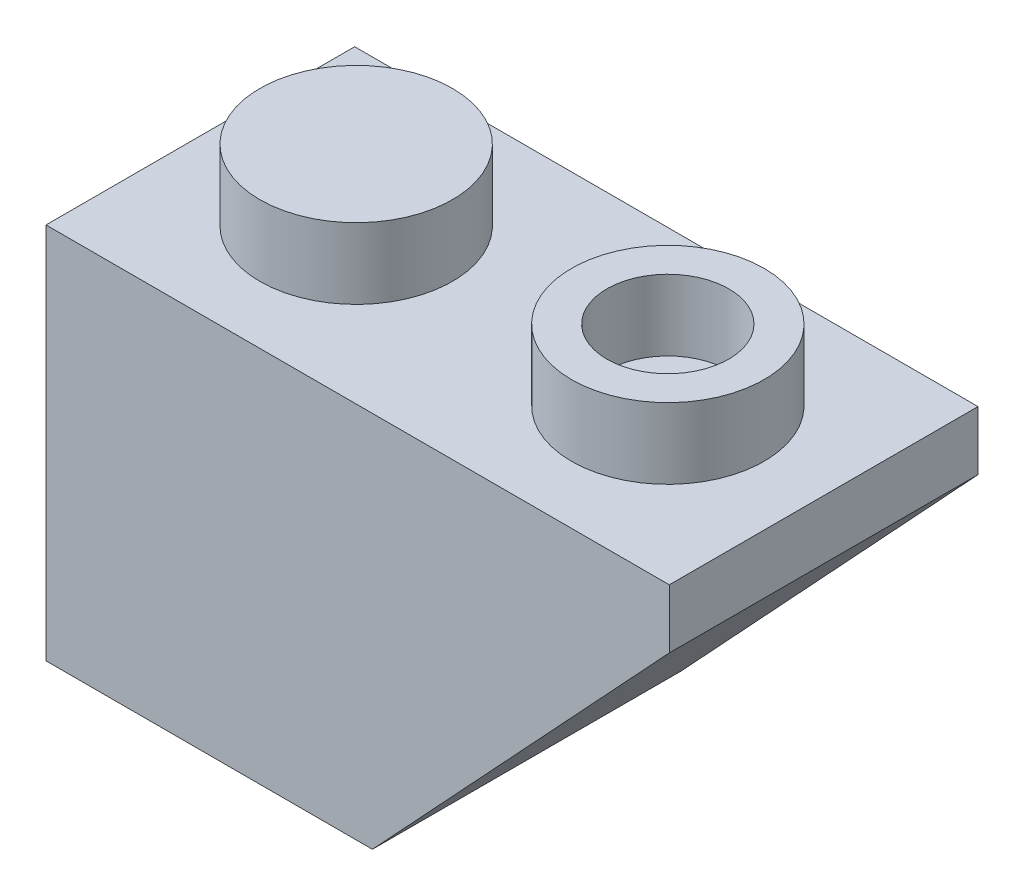
SolidWorks part; units mm, degrees
ref_plane "Front Plane" through (0, 0, 0) normal (0, 0, 1) x (1, 0, 0)
ref_plane "Top Plane" through (0, 0, 0) normal (0, 1, 0) x (1, 0, 0)
ref_plane "Right Plane" through (0, 0, 0) normal (1, 0, 0) x (0, 0, -1)
sketch "Sketch2" plane through (0, 0, 0) normal (0, 0, 1) x (1, 0, 0)
  line L0 (0, 9.6) -> (0, 0)
  line L1 (0, 0) -> (8.3, 0)
  line L2 (8.3, 0) -> (15.85, 8.1)
  line L3 (15.85, 8.1) -> (15.85, 9.6)
  line L4 (15.85, 9.6) -> (0, 9.6)
  dimension "D1" = 9.6
  dimension "D2" = 15.85
  dimension "D3" = 1.5
  dimension "D4" = 8.3
extrude "Boss-Extrude1" add sketch "Sketch2" against normal blind 7.85
sketch "Sketch5" plane through (0, 0, 0) normal (0, -1, 0) x (1, 0, 0)
  line L0 (1.5, -1.5) -> (1.5, -6.35)
  line L1 (1.5, -6.35) -> (6.8, -6.35)
  line L2 (1.5, -1.5) -> (6.8, -1.5)
  line L3 (6.8, -1.5) -> (6.8, -6.35)
  line L4 (0, 0) -> (8.3, 0) construction
  line L5 (8.3, -7.85) -> (8.3, 0) construction
  line L6 (0, -7.85) -> (0, 0) construction
  line L7 (0, -7.85) -> (8.3, -7.85) construction
  dimension "D1" = 1.5
  dimension "D2" = 1.5
  dimension "D3" = 1.5
  dimension "D4" = 1.5
extrude "Cut-Extrude1" cut sketch "Sketch5" against normal offset from surface (8.1 mm away) 1.5 up to face at (7.925, 9.6, -3.925)
sketch "Sketch6" plane through (0, 9.6, 0) normal (0, 1, 0) x (1, 0, 0)
  line L0 (15.85, 0) -> (0, 0) construction
  line L2 (0, 7.85) -> (0, 0) construction
  circle A0 centre (3.9625, 3.925) radius 2.45
  circle A1 centre (11.8875, 3.925) radius 2.45
  circle A2 centre (11.8875, 3.925) radius 1.55
  dimension "D3" = 7.925
  dimension "D4" = 3.9625
  dimension "D5" = 4.9
  dimension "D6" = 4.9
  dimension "D7" = 3.1
  dimension "D1" = 3.925
  dimension "D2" = 3.925
extrude "Boss-Extrude3" add sketch "Sketch6" along normal blind 1.8
sketch "Sketch7" plane through (0, 8.1, 0) normal (0, -1, 0) x (1, 0, 0)
  circle A0 centre (3.9625, -3.925) radius 0.95
  dimension "D1" = 1.9
extrude "Cut-Extrude2" cut sketch "Sketch7" against normal offset from surface (1.8 mm away) 1.5 up to face at (3.9625, 11.4, -1.475)
